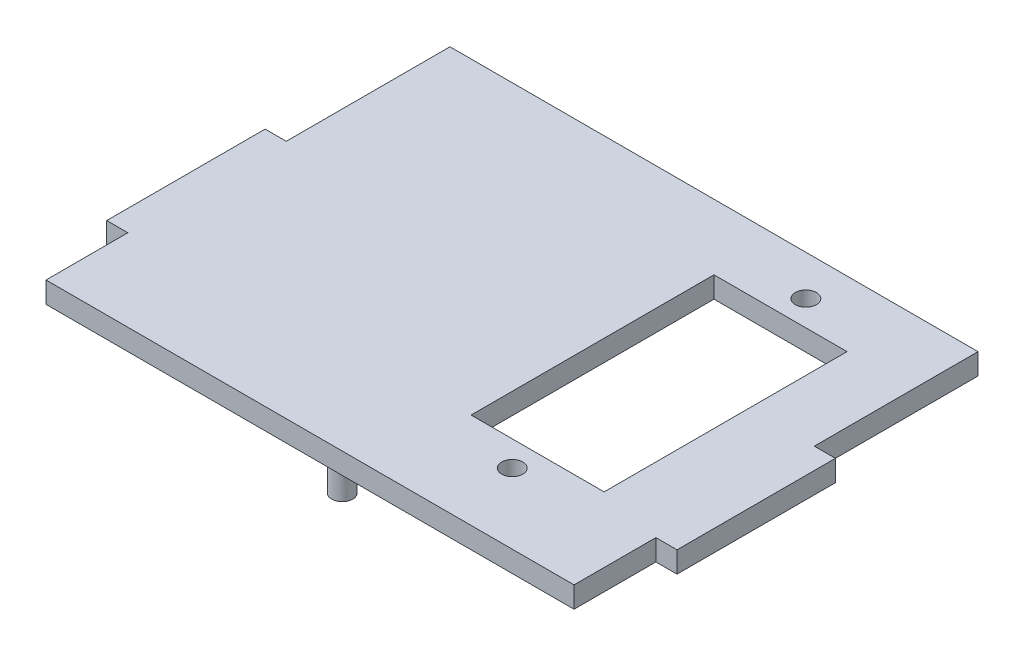
SolidWorks part; units mm, degrees
ref_plane "Front Plane" through (0, 0, 0) normal (0, 0, 1) x (1, 0, 0)
ref_plane "Top Plane" through (0, 0, 0) normal (0, 1, 0) x (1, 0, 0)
ref_plane "Right Plane" through (0, 0, 0) normal (1, 0, 0) x (0, 0, -1)
sketch "Sketch1" plane through (0, 0, 0) normal (0, 1, 0) x (1, 0, 0)
  line L0 (-38.5795, 0) -> (41.6132, 0) construction
  line L1 (-25, 23) -> (25, 23)
  line L2 (-25, 23) -> (-25, 7.5)
  line L3 (-25, -23) -> (25, -23)
  line L4 (25, 23) -> (25, 7.5)
  line L5 (25, -7.5) -> (25, -23)
  line L6 (31.1346, -15) -> (-36.746, -15) construction
  line L7 (0, 34.8382) -> (0, -34.2375) construction
  line L8 (-27, 7.5) -> (-25, 7.5)
  line L9 (-27, 7.5) -> (-27, -7.5)
  line L10 (-27, -7.5) -> (-25, -7.5)
  line L14 (27, -7.5) -> (25, -7.5)
  line L15 (27, 7.5) -> (27, -7.5)
  line L16 (27, 7.5) -> (25, 7.5)
  line L17 (-12.5, 34.8382) -> (-12.5, -34.2375) construction
  line L18 (6.2, 16.8) -> (6.2, 6.2)
  line L20 (6.2, 16.8) -> (18.8, 16.8)
  line L21 (18.8, 16.8) -> (18.8, 6.2)
  line L23 (6.2, -6.2) -> (18.8, -6.2)
  line L24 (12.5, -6.2) -> (12.5, 16.8) construction
  line L27 (6.2, 6.2) -> (6.2, -6.2)
  line L28 (-25, -7.5) -> (-25, -23)
  line L29 (18.8, 6.2) -> (18.8, -6.2)
  circle A0 centre (12.5, 19.2) radius 1
  circle A1 centre (12.5, -8.6) radius 1
  point P0 (0, 0)
  point P12 (-26, 0)
  point P23 (12.5, 0)
  point P27 (12.5, 28.796)
  point P29 (12.5, 0)
  dimension "D6" = 2
  dimension "D1" = 46
  dimension "D2" = 50
  dimension "D3" = 15
  dimension "D4" = 2
  dimension "D5" = 12.5
  dimension "D7" = 2.4
  dimension "D8" = 67.8806
  dimension "D9" = 15
extrude "Boss-Extrude1" add sketch "Sketch1" along normal blind 2
sketch "Sketch2" plane through (0, 0, 0) normal (0, -1, 0) x (1, 0, 0)
  line L0 (-12.5, -34.8382) -> (-12.5, 34.2375) construction
  circle A0 centre (-12.5, -0.3003) radius 1
extrude "Boss-Extrude2" add sketch "Sketch2" along normal blind 17
sketch "Sketch3" plane through (0, 0, 0) normal (0, -1, 0) x (1, 0, 0)
  line L1 (-25, 23) -> (25, 23)
  line L2 (-25, 23) -> (-25, 15.25)
  line L3 (-25, 15.25) -> (25, 15.25)
  line L4 (25, 23) -> (25, 15.25)
  line L5 (-25, 23) -> (25, 15.25) construction
  line L6 (-25, 15.25) -> (25, 23) construction
  line L7 (25, 7.5) -> (25, 23) construction
  point P4 (0, 19.125)
  dimension "D1" = 7.75
  dimension "D2" = 50
extrude "Cut-Extrude1" cut sketch "Sketch3" against normal up to surface (2 mm away) up to face at (12.5, 2, -18.2)
